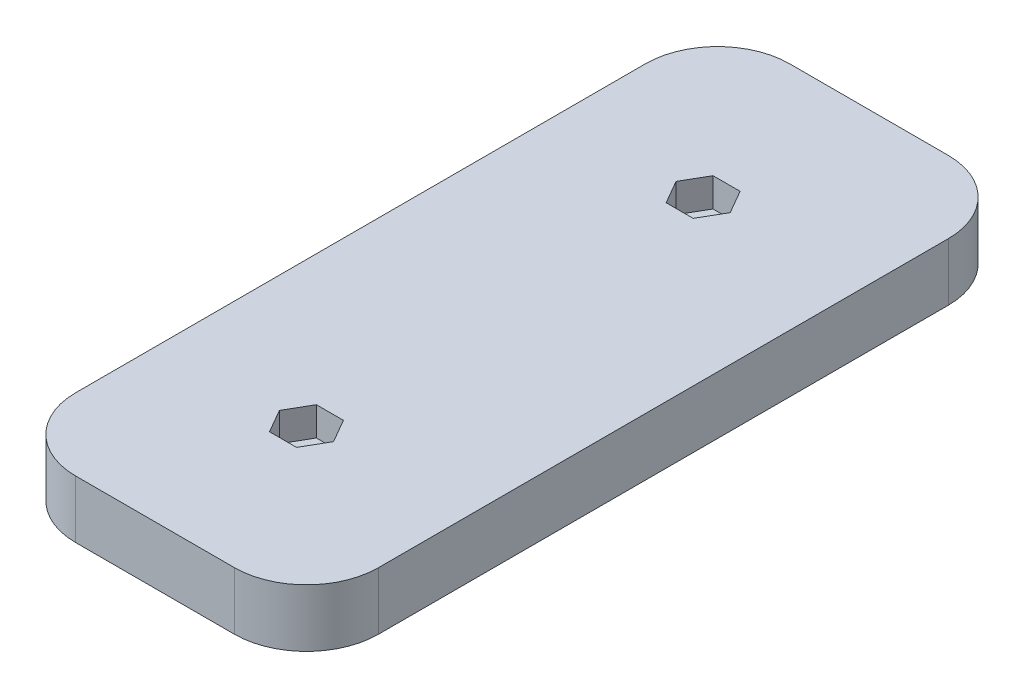
SolidWorks part; units mm, degrees
ref_plane "Front Plane" through (0, 0, 0) normal (0, 0, 1) x (1, 0, 0)
ref_plane "Top Plane" through (0, 0, 0) normal (0, 1, 0) x (1, 0, 0)
ref_plane "Right Plane" through (0, 0, 0) normal (1, 0, 0) x (0, 0, -1)
sketch "Sketch1" plane through (0, 0, 0) normal (0, 1, 0) x (1, 0, 0)
  line L0 (0, 49.5) -> (42, 49.5) construction
  line L1 (0, 0) -> (42, 0)
  line L2 (0, 0) -> (0, 99)
  line L3 (0, 99) -> (42, 99)
  line L4 (42, 0) -> (42, 99)
  line L5 (0, 0) -> (42, 99) construction
  line L6 (0, 99) -> (42, 0) construction
  circle A0 centre (20, 77) radius 2
  circle A1 centre (20, 22) radius 2
  point P4 (21, 49.5)
  dimension "D3" = 4
  dimension "D1" = 42
  dimension "D2" = 99
  dimension "D4" = 20
  dimension "D5" = 55
extrude "Boss-Extrude1" add sketch "Sketch1" along normal blind 8 contours L1 L4 L3 L2 A0 A1
sketch "Sketch2" plane through (0, 8, 0) normal (0, 1, 0) x (1, 0, 0)
  line L1 (21.8764, 80.25) -> (18.1236, 80.25)
  line L2 (18.1236, 80.25) -> (16.2472, 77)
  line L3 (16.2472, 77) -> (18.1236, 73.75)
  line L4 (18.1236, 73.75) -> (21.8764, 73.75)
  line L5 (21.8764, 73.75) -> (23.7528, 77)
  line L6 (23.7528, 77) -> (21.8764, 80.25)
  line L7 (21.8764, 18.75) -> (23.7528, 22)
  line L8 (23.7528, 22) -> (21.8764, 25.25)
  line L9 (21.8764, 25.25) -> (18.1236, 25.25)
  line L10 (18.1236, 25.25) -> (16.2472, 22)
  line L11 (16.2472, 22) -> (18.1236, 18.75)
  line L12 (18.1236, 18.75) -> (21.8764, 18.75)
  circle A0 centre (20, 77) radius 3.25 construction
  circle A1 centre (20, 22) radius 3.25 construction
  point P10 (0, 0)
  point P19 (28.0635, 22.965)
  dimension "D1" = 6.5
  dimension "D2" = 6.5
extrude "Cut-Extrude1" cut sketch "Sketch2" against normal blind 4 contours L8 L9 L10 L11 L12 L7 | L6 L1 L2 L3 L4 L5
fillet "Fillet1" radius 10 4 edges at (0, 4, -99) (42, 4, -99) (0, 4, 0) (42, 4, 0)
